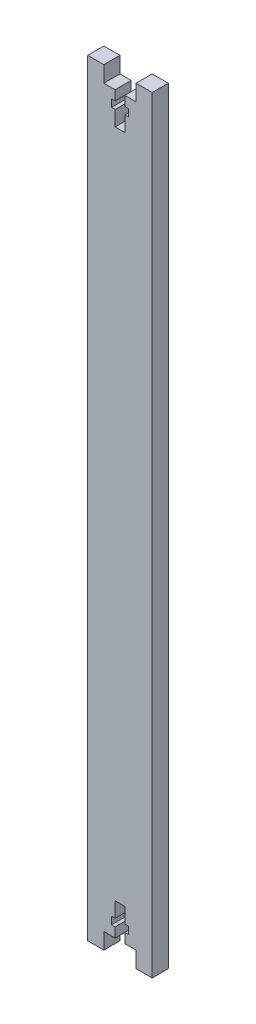
SolidWorks part; units mm, degrees
ref_plane "Front Plane" through (0, 0, 0) normal (0, 0, 1) x (1, 0, 0)
ref_plane "Top Plane" through (0, 0, 0) normal (0, 1, 0) x (1, 0, 0)
ref_plane "Right Plane" through (0, 0, 0) normal (1, 0, 0) x (0, 0, -1)
sketch "Sketch1" plane through (0, 0, 0) normal (0, 0, 1) x (1, 0, 0)
  line L2 (10, 233) -> (10, 221.7792) construction
  line L3 (11.5, 233) -> (15, 233)
  line L4 (15, 238) -> (20, 238)
  line L5 (20, 238) -> (20, 233)
  line L6 (15, 238) -> (15, 233)
  line L7 (8.5, 233) -> (5, 233)
  line L8 (5, 233) -> (5, 238)
  line L9 (5, 238) -> (0, 238)
  line L10 (0, 238) -> (0, 233)
  line L11 (11.5, 233) -> (8.5, 233) construction
  line L12 (8.5, 233) -> (8.5, 230)
  line L13 (8.5, 227.7) -> (7.4, 227.7)
  line L14 (12.6, 230) -> (12.6, 227.7)
  line L15 (7.4, 230) -> (8.5, 230)
  line L16 (8.5, 227.7) -> (8.5, 223)
  line L17 (8.5, 223) -> (11.5, 223)
  line L18 (11.5, 223) -> (11.5, 227.7)
  line L19 (11.5, 230) -> (12.6, 230)
  line L20 (7.4, 227.7) -> (7.4, 230)
  line L21 (12.6, 227.7) -> (11.5, 227.7)
  line L22 (11.5, 230) -> (11.5, 233)
  line L23 (10, 223) -> (10, 233) construction
  line L24 (10, 5) -> (10, 16.2208) construction
  line L25 (8.5, 5) -> (5, 5)
  line L26 (5, 0) -> (0, 0)
  line L27 (0, 0) -> (0, 5)
  line L28 (5, 0) -> (5, 5)
  line L29 (11.5, 5) -> (15, 5)
  line L30 (15, 5) -> (15, 0)
  line L31 (15, 0) -> (20, 0)
  line L32 (20, 0) -> (20, 5)
  line L33 (8.5, 5) -> (11.5, 5) construction
  line L34 (11.5, 5) -> (11.5, 8)
  line L35 (11.5, 10.3) -> (12.6, 10.3)
  line L36 (7.4, 8) -> (7.4, 10.3)
  line L37 (12.6, 8) -> (11.5, 8)
  line L38 (11.5, 10.3) -> (11.5, 15)
  line L39 (11.5, 15) -> (8.5, 15)
  line L40 (8.5, 15) -> (8.5, 10.3)
  line L41 (8.5, 8) -> (7.4, 8)
  line L42 (12.6, 10.3) -> (12.6, 8)
  line L43 (7.4, 10.3) -> (8.5, 10.3)
  line L44 (8.5, 8) -> (8.5, 5)
  line L45 (10, 15) -> (10, 5) construction
  line L46 (0, 233) -> (0, 5)
  line L47 (20, 5) -> (20, 233)
  point P5 (2.5, 238)
  dimension "D1" = 238
  dimension "D2" = 10
  dimension "D3" = 5
  dimension "D4" = 5
  dimension "D5" = 5.2
  dimension "D6" = 3
  dimension "D7" = 2.3
  dimension "D8" = 3
  dimension "D9" = 10
  dimension "D10" = 10
  dimension "D11" = 5
  dimension "D12" = 5
  dimension "D13" = 5.2
  dimension "D14" = 3
  dimension "D15" = 2.3
  dimension "D16" = 3
  dimension "D17" = 10
extrude "Boss-Extrude1" add sketch "Sketch1" along normal blind 5
